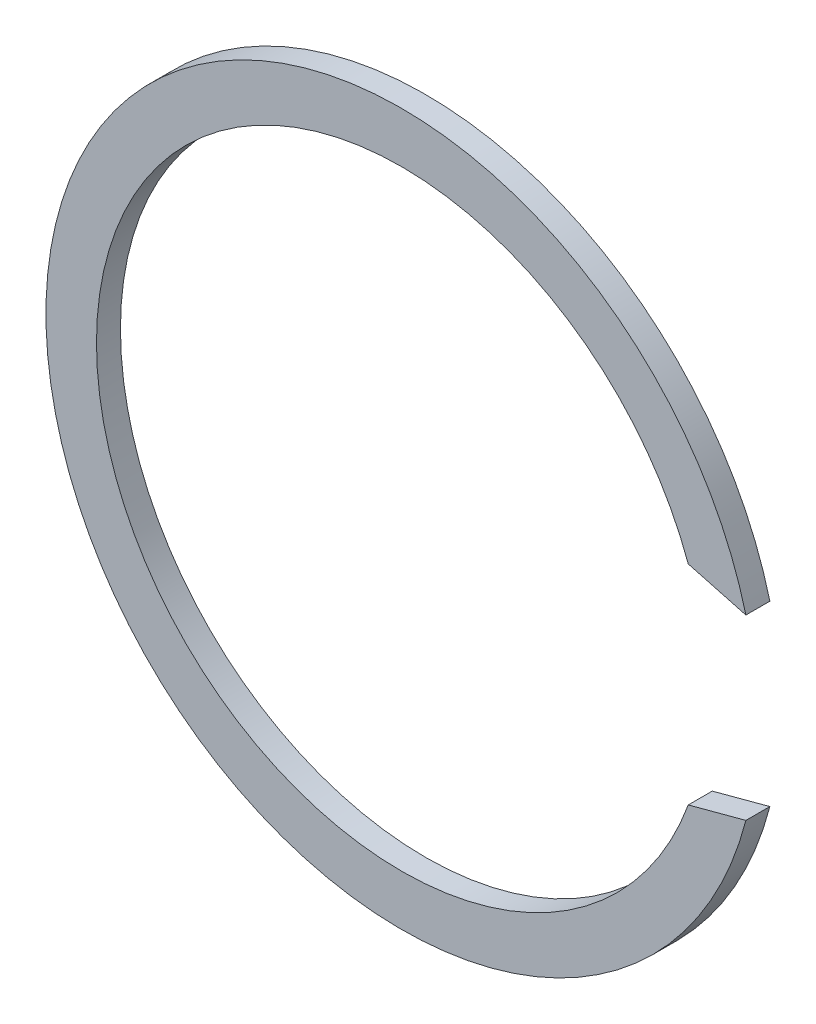
SolidWorks part; units mm, degrees
ref_plane "Front" through (0, 0, 0) normal (0, 0, 1) x (1, 0, 0)
ref_plane "Top" through (0, 0, 0) normal (0, 1, 0) x (1, 0, 0)
ref_plane "Right" through (0, 0, 0) normal (1, 0, 0) x (0, 0, -1)
sketch "Sketch1" plane through (0, 0, 0) normal (0, 0, 1) x (1, 0, 0)
  line L0 (-35.755, 0) -> (35.755, 0) construction
  line L1 (0, 8.9388) -> (35.755, 8.9388) construction
  line L2 (0, -8.9388) -> (35.755, -8.9388) construction
  line L3 (0, 0) -> (0, 8.9388) construction
  line L4 (0, 8.9388) -> (0, 17.8775) construction
  line L5 (0, 17.8775) -> (0, 26.8163) construction
  line L6 (0, 26.8163) -> (0, 35.755) construction
  line L7 (34.6196, 8.9388) -> (0, 18.2151) construction
  line L8 (34.6196, -8.9388) -> (0, -18.2151) construction
  line L9 (0, 0) -> (-21.6905, -21.6905) construction
  line L10 (0, 0) -> (14.3658, -14.3658) construction
  line L11 (21.6905, -21.6905) -> (25.2826, -25.2826) construction
  circle A0 centre (0, 0) radius 30.675 construction
  circle A1 centre (0, 0) radius 35.755 construction
  point P6 (0, 30.675)
  point P22 (0, 35.755)
  point P25 (-21.6905, -21.6905)
  dimension "D1" = 15
  dimension "Ring ID" = 61.35
  dimension "Section" = 5.08
  dimension "D2" = 45
sketch "Sketch3" plane through (0, 0, 0) normal (0, 1, 0) x (1, 0, 0)
  line L0 (-35.755, 1.205) -> (-35.755, -1.205) construction
  point P3 (-35.755, 0)
  dimension "Ring Thickness" = 2.41
sketch "Sketch2" plane through (0, 0, 0) normal (0, 0, 1) x (1, 0, 0)
  line L0 (34.6196, 8.9388) -> (0, 18.2151) construction
  line L1 (34.6196, -8.9388) -> (0, -18.2151) construction
  line L2 (34.6196, 8.9388) -> (28.8251, 10.4914)
  line L3 (34.6196, -8.9388) -> (28.8251, -10.4914)
  circle A0 centre (0, 0) radius 35.755 construction
  circle A1 centre (0, 0) radius 30.675 construction
  arc A2 (34.6196, 8.9388) -> (34.6196, -8.9388) centre (0, 0) ccw
  arc A3 (28.8251, 10.4914) -> (28.8251, -10.4914) centre (0, 0) ccw
extrude "Boss-Extrude1" add sketch "Sketch2" along normal mid plane 2.41
equation "\"D1@Boss-Extrude1\"= \"Ring Thickness@Sketch3\""
